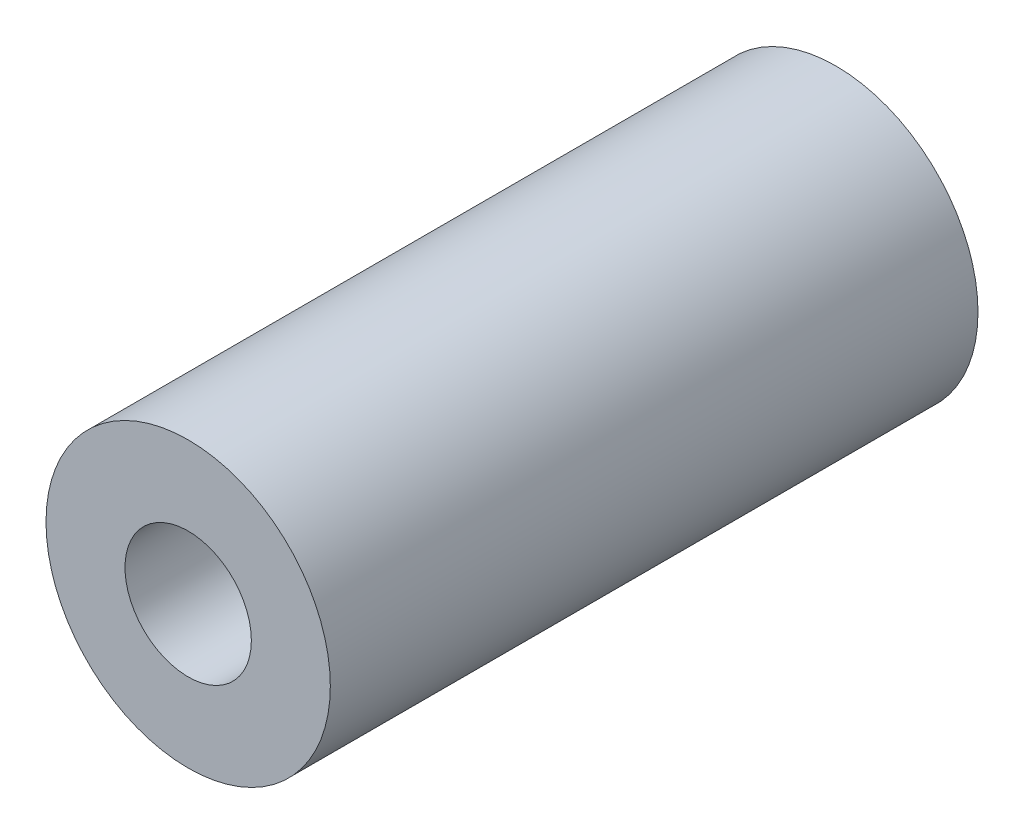
SolidWorks part; units mm, degrees
ref_plane "Ebene vorne" through (0, 0, 0) normal (0, 0, 1) x (1, 0, 0)
ref_plane "Ebene oben" through (0, 0, 0) normal (0, 1, 0) x (1, 0, 0)
ref_plane "Ebene rechts" through (0, 0, 0) normal (1, 0, 0) x (0, 0, -1)
sketch "Skizze1" plane through (0, 0, 0) normal (0, 0, 1) x (1, 0, 0)
  circle A0 centre (0, 0) radius 2
  circle A1 centre (0, 0) radius 4.5
  dimension "D1" = 9
  dimension "D2" = 4
extrude "Aufsatz-Linear austragen1" add sketch "Skizze1" along normal blind 20.5
